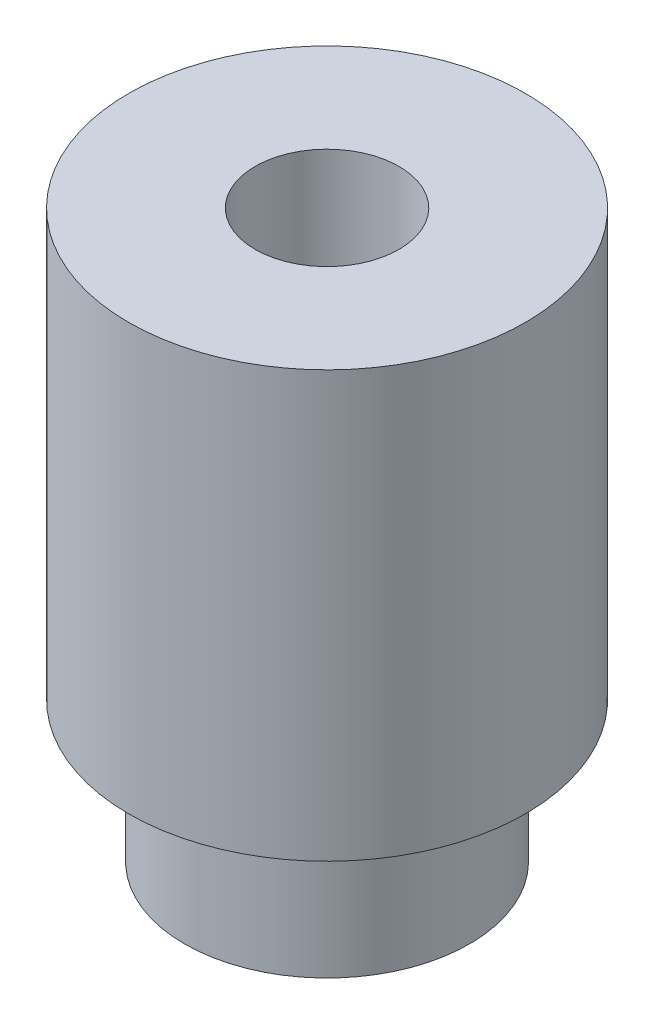
SolidWorks part; units mm, degrees
material "AISI 1020 Steel, Cold Rolled"
ref_plane "Front Plane" through (0, 0, 0) normal (0, 0, 1) x (1, 0, 0)
ref_plane "Top Plane" through (0, 0, 0) normal (0, 1, 0) x (1, 0, 0)
ref_plane "Right Plane" through (0, 0, 0) normal (1, 0, 0) x (0, 0, -1)
sketch "Sketch1" plane through (0, 0, 0) normal (0, 1, 0) x (1, 0, 0)
  circle A0 centre (0, 0) radius 10.033
  dimension "D1" = 20.066
extrude "Boss-Extrude1" add sketch "Sketch1" along normal blind 9.906
sketch "Sketch2" plane through (0, 9.906, 0) normal (0, 1, 0) x (1, 0, 0)
  circle A0 centre (0, 0) radius 13.97
  dimension "D1" = 27.94
extrude "Boss-Extrude2" add sketch "Sketch2" along normal blind 29.972
sketch "Sketch3" plane through (0, 39.878, 0) normal (0, 1, 0) x (1, 0, 0)
  circle A0 centre (0, 0) radius 5.0673
  dimension "D1" = 10.1346
extrude "Cut-Extrude1" cut sketch "Sketch3" against normal through all
